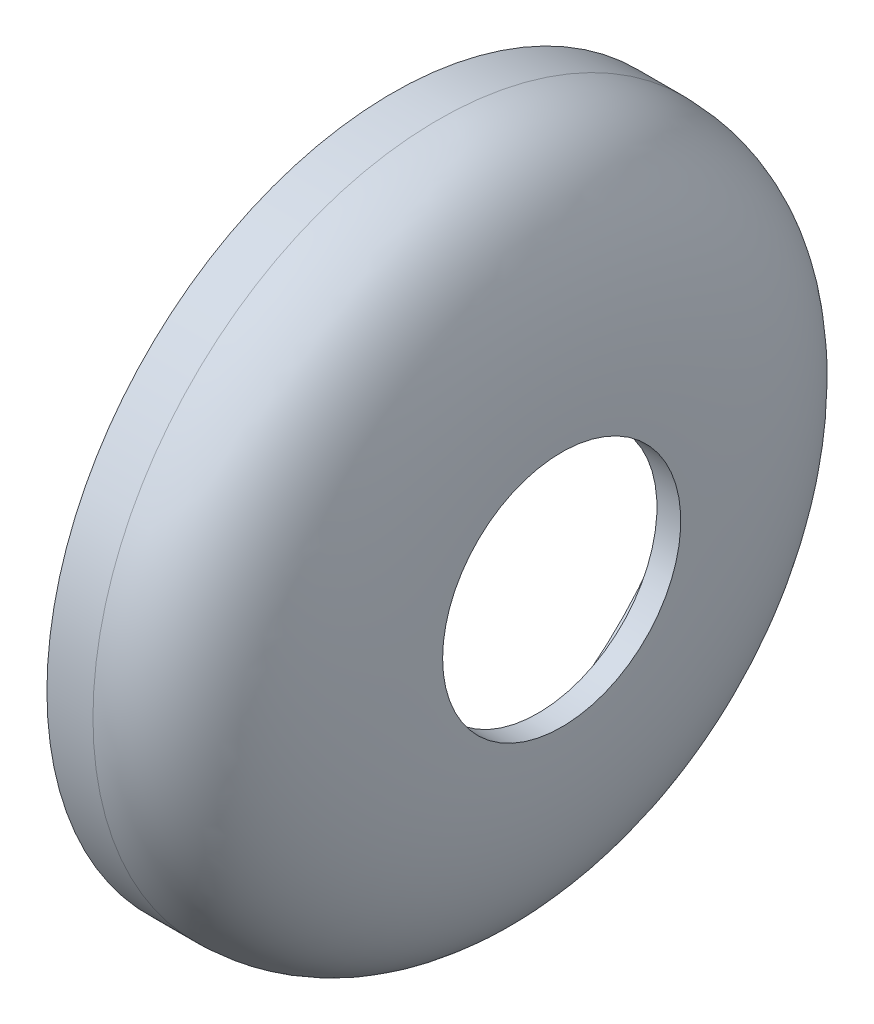
SolidWorks part; units mm, degrees
ref_plane "Front Plane" through (0, 0, 0) normal (0, 0, 1) x (1, 0, 0)
ref_plane "Top Plane" through (0, 0, 0) normal (0, 1, 0) x (1, 0, 0)
ref_plane "Right Plane" through (0, 0, 0) normal (1, 0, 0) x (0, 0, -1)
sketch "Sketch1" plane through (0, 0, 0) normal (0, 0, 1) x (1, 0, 0)
  line L0 (0, 27) -> (0, 29)
  line L1 (0, 29) -> (3.8655, 29)
  line L3 (3.8655, 27) -> (0, 27)
  line L4 (3.8655, 27) -> (12.23, 27) construction
  line L5 (12.23, 27) -> (12.23, 10) construction
  line L6 (3.8655, 29) -> (14.23, 29) construction
  line L7 (14.23, 29) -> (14.23, 10) construction
  line L8 (12.23, 10) -> (14.23, 10)
  spline S0 degree 2 poles (3.8655, 27) (12.23, 27) (12.23, 10) knots 0 0 0 1 1 1
  spline S1 degree 2 poles (3.8655, 29) (14.23, 29) (14.23, 10) knots 0 0 0 1 1 1
  dimension "D1" = 2
  dimension "D2" = 2
  dimension "D3" = 10
  dimension "D4" = 29
  dimension "D5" = 14.23
sketch "Sketch2" plane through (0, 0, 0) normal (0, 0, 1) x (1, 0, 0)
  line L0 (-5.3273, 0) -> (17.7833, 0) construction
revolve "Revolve1" add sketch "Sketch1" angle 360 about L0
